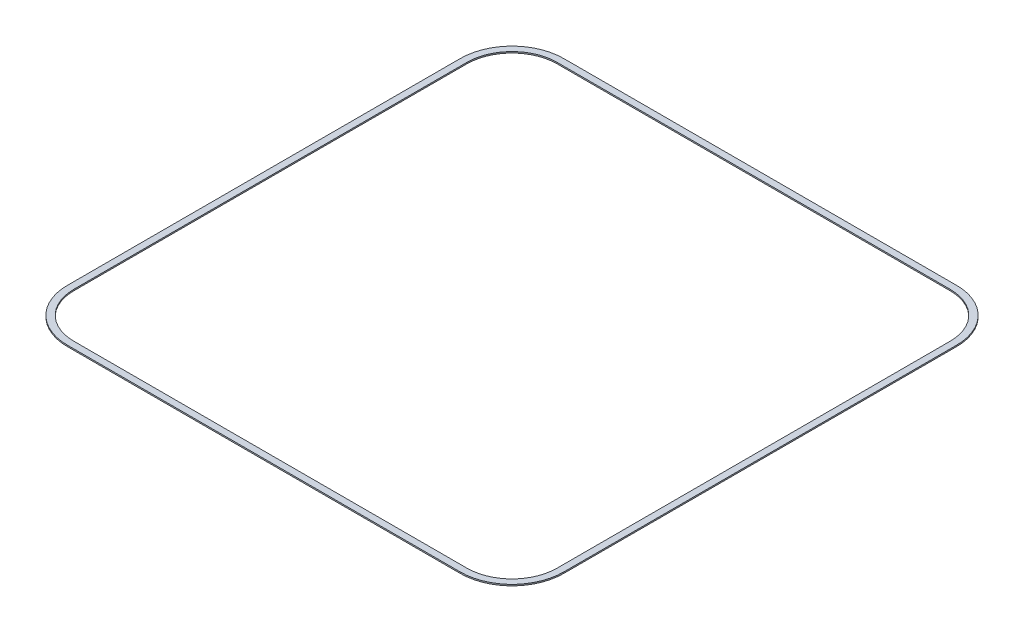
SolidWorks part; units mm, degrees
ref_plane "Front Plane" through (0, 0, 0) normal (0, 0, 1) x (1, 0, 0)
ref_plane "Top Plane" through (0, 0, 0) normal (0, 1, 0) x (1, 0, 0)
ref_plane "Right Plane" through (0, 0, 0) normal (1, 0, 0) x (0, 0, -1)
sketch "Sketch1" plane through (0, 0, 0) normal (0, 1, 0) x (1, 0, 0)
  line L0 (0, -240.0766) -> (0, 240.0766) construction
  line L1 (-202.6279, 0) -> (202.6279, 0) construction
  line L2 (-148.5, 182.5) -> (148.5, 182.5)
  line L3 (182.5, 148.5) -> (182.5, -148.5)
  line L4 (-182.5, 148.5) -> (-182.5, -148.5)
  line L5 (-148.5, -182.5) -> (148.5, -182.5)
  line L6 (187.5, 148.5) -> (187.5, -148.5)
  line L7 (148.5, -148.5) -> (187.5, -148.5) construction
  line L8 (148.5, 148.5) -> (212.4844, 148.5) construction
  line L9 (148.5, 187.5) -> (-148.5, 187.5)
  line L10 (-187.5, 148.5) -> (-187.5, -148.5)
  line L11 (148.5, -187.5) -> (-148.5, -187.5)
  circle A0 centre (148.5, 148.5) radius 34 construction
  circle A1 centre (-148.5, 148.5) radius 34 construction
  circle A2 centre (-148.5, -148.5) radius 34 construction
  circle A3 centre (148.5, -148.5) radius 34 construction
  arc A4 (-148.5, 182.5) -> (-182.5, 148.5) centre (-148.5, 148.5) ccw
  arc A5 (148.5, 182.5) -> (182.5, 148.5) centre (148.5, 148.5) cw
  arc A6 (182.5, -148.5) -> (148.5, -182.5) centre (148.5, -148.5) cw
  arc A7 (-148.5, -182.5) -> (-182.5, -148.5) centre (-148.5, -148.5) cw
  arc A8 (148.5, 187.5) -> (187.5, 148.5) centre (148.5, 148.5) cw
  arc A9 (-148.5, 187.5) -> (-187.5, 148.5) centre (-148.5, 148.5) ccw
  arc A10 (-148.5, -187.5) -> (-187.5, -148.5) centre (-148.5, -148.5) cw
  arc A11 (148.5, -187.5) -> (187.5, -148.5) centre (148.5, -148.5) ccw
  point P6 (0, 0)
  point P10 (0, 0)
  point P27 (0, 187.5)
  point P30 (187.5, 0)
  point P34 (-187.5, 0)
  dimension "D3" = 68
  dimension "D4" = 5
  dimension "D1" = 297
  dimension "D2" = 297
extrude "Boss-Extrude1" add sketch "Sketch1" along normal blind 1
